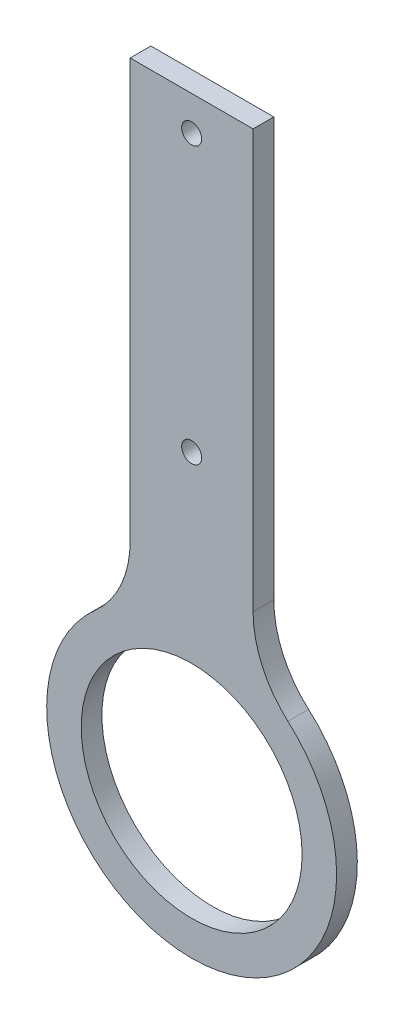
SolidWorks part; units mm, degrees
material "Thornel Mat VMA"
ref_plane "前视基准面" through (0, 0, 0) normal (0, 0, 1) x (1, 0, 0)
ref_plane "上视基准面" through (0, 0, 0) normal (0, 1, 0) x (1, 0, 0)
ref_plane "右视基准面" through (0, 0, 0) normal (1, 0, 0) x (0, 0, -1)
sketch "草图1" plane through (0, 0, 0) normal (0, 0, 1) x (1, 0, 0)
  circle A0 centre (0, 0) radius 21
  circle A9 centre (0, 0) radius 16
  dimension "D1" = 32
  dimension "D2" = 42
extrude "凸台-拉伸1" add sketch "草图1" along normal blind 3
sketch "草图2" plane through (0, 0, 0) normal (0, 0, 1) x (1, 0, 0)
  line L0 (0, 12.5) -> (0, 87.5) construction
  line L1 (-8.9, 12.5) -> (8.9, 12.5)
  line L2 (-8.9, 12.5) -> (-8.9, 87.5)
  line L3 (-8.9, 87.5) -> (8.9, 87.5)
  line L4 (8.9, 12.5) -> (8.9, 87.5)
  line L5 (-8.9, 12.5) -> (8.9, 87.5) construction
  line L6 (-8.9, 87.5) -> (8.9, 12.5) construction
  circle A1 centre (0, 42.5) radius 1.45
  circle A2 centre (0, 82.5) radius 1.45
  point P0 (0, 50)
  dimension "D4" = 2.9
  dimension "D1" = 12.5
  dimension "D2" = 17.8
  dimension "D3" = 75
  dimension "D5" = 40
  dimension "D6" = 5
extrude "凸台-拉伸2" add sketch "草图2" along normal blind 3
sketch "草图3" plane through (0, 0, 3) normal (0, 0, 1) x (1, 0, 0)
  circle A1 centre (0, 0) radius 16
  arc A2 (-8.9, 13.2962) -> (8.9, 13.2962) centre (0, 0) ccw construction
extrude "切除-拉伸1" cut sketch "草图3" against normal through all
fillet "圆角1" radius 15 2 edges at (-8.9, 19.0208, 1.5) (8.9, 19.0208, 1.5)
